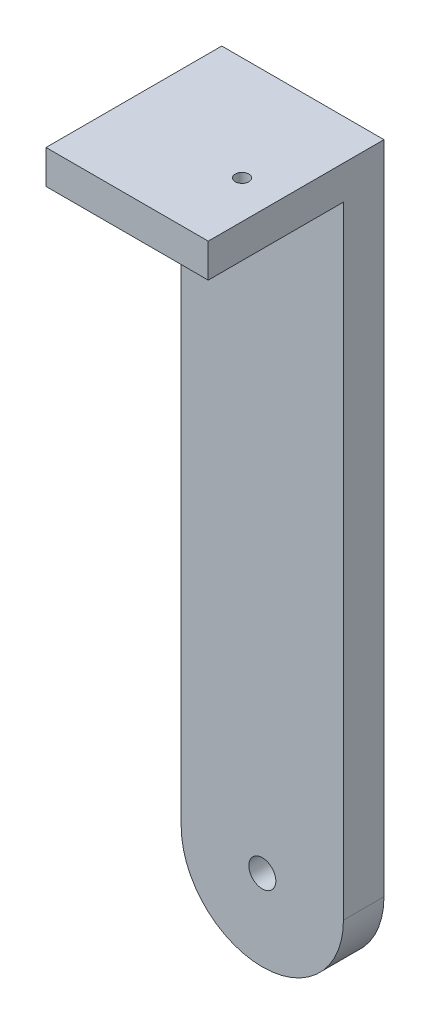
SolidWorks part; units mm, degrees
ref_plane "Front Plane" through (0, 0, 0) normal (1, 0, 0) x (0, 1, 0)
ref_plane "Top Plane" through (0, 0, 0) normal (0, 0, 1) x (0, 1, 0)
ref_plane "Right Plane" through (0, 0, 0) normal (0, 1, 0) x (-1, 0, 0)
sketch "Sketch1" plane through (0, 0, 0) normal (0, 0, 1) x (0, 1, 0)
  line L0 (0, 60) -> (400, 60)
  line L1 (0, -60) -> (400, -60)
  line L2 (400, 60) -> (460, 60)
  line L3 (460, 60) -> (460, -60)
  line L4 (460, -60) -> (400, -60)
  arc A0 (0, 60) -> (0, -60) centre (0, 0) ccw
  circle A2 centre (0, 0) radius 10
  dimension "D1" = 120
  dimension "D2" = 460
  dimension "D4" = 20
extrude "Boss-Extrude1" add sketch "Sketch1" along normal blind 30
sketch "Sketch2" plane through (0, 0, 30) normal (0, 0, 1) x (1, 0, 0)
  line L1 (-60, 460) -> (60, 460)
  line L2 (-60, 460) -> (-60, 485)
  line L3 (-60, 485) -> (60, 485)
  line L4 (60, 460) -> (60, 485)
  dimension "D1" = 25
  dimension "D2" = 120
extrude "Boss-Extrude2" add sketch "Sketch2" along normal blind 100 and the other way blind 30
sketch "Sketch3" plane through (0, 460, 0) normal (0, -1, 0) x (1, 0, 0)
  line L0 (60, 30) -> (60, 130) construction
  line L1 (-60, 130) -> (60, 130) construction
  circle A0 centre (32, 77) radius 5
  dimension "D1" = 10
  dimension "D2" = 28
  dimension "D3" = 53
extrude "Cut-Extrude1" cut sketch "Sketch3" against normal blind 70
